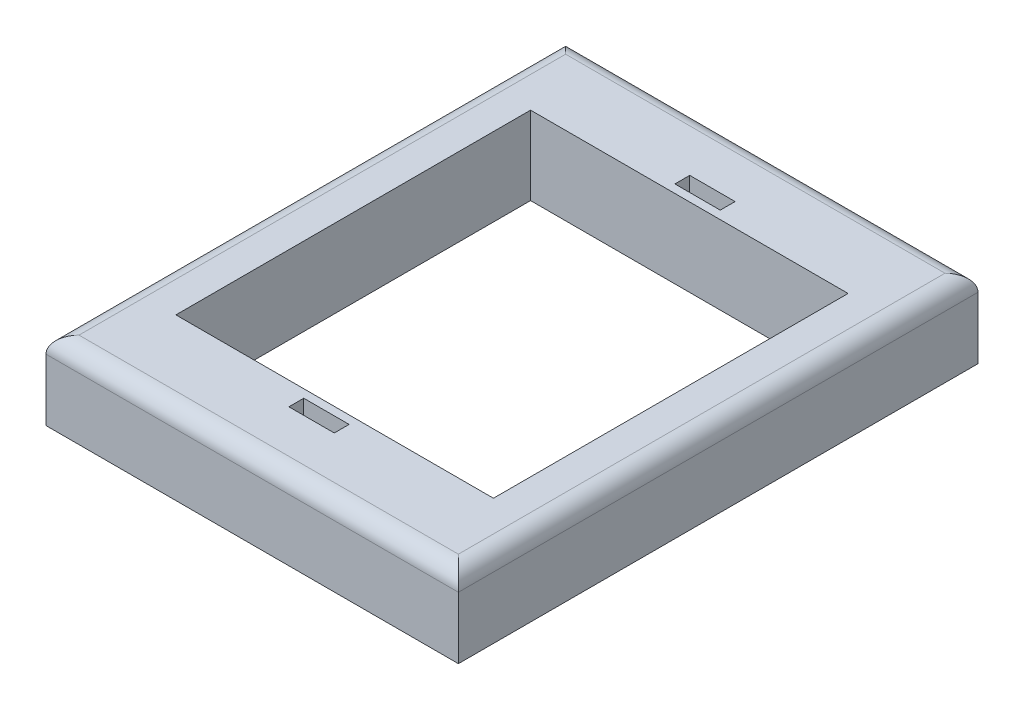
SolidWorks part; units mm, degrees
ref_plane "Front Plane" through (0, 0, 0) normal (0, 0, 1) x (1, 0, 0)
ref_plane "Top Plane" through (0, 0, 0) normal (0, 1, 0) x (1, 0, 0)
ref_plane "Right Plane" through (0, 0, 0) normal (1, 0, 0) x (0, 0, -1)
sketch "Sketch1" plane through (0, 0, 0) normal (0, 1, 0) x (1, 0, 0)
  line L0 (-4.2097, 29.6431) -> (-42.7097, 29.6431)
  line L1 (-42.7097, 29.6431) -> (-42.7097, -13.3569)
  line L2 (-42.7097, -13.3569) -> (-4.2097, -13.3569)
  line L3 (-4.2097, 29.6431) -> (-4.2097, -13.3569)
  line L4 (-48.4597, 39.6431) -> (1.5403, 39.6431)
  line L5 (1.5403, 39.6431) -> (1.5403, -23.3569)
  line L6 (1.5403, -23.3569) -> (-48.4597, -23.3569)
  line L7 (-48.4597, -23.3569) -> (-48.4597, 39.6431)
  dimension "D1" = 43
  dimension "D2" = 38.5
  dimension "D3" = 50
  dimension "D4" = 5.75
  dimension "D5" = 10
  dimension "D6" = 10
extrude "Boss-Extrude1" add sketch "Sketch1" along normal blind 9.5
sketch "Sketch2" plane through (0, 9.5, 0) normal (0, 1, 0) x (1, 0, 0)
  line L0 (-42.7097, -13.3569) -> (-4.2097, -13.3569) construction
  line L1 (-26.2097, 32.4431) -> (-20.7097, 32.4431)
  line L2 (-26.2097, 32.4431) -> (-26.2097, 30.6431)
  line L3 (-26.2097, 30.6431) -> (-20.7097, 30.6431)
  line L4 (-20.7097, 32.4431) -> (-20.7097, 30.6431)
  line L5 (-26.2097, -14.3569) -> (-20.7097, -14.3569)
  line L6 (-26.2097, -14.3569) -> (-26.2097, -16.1569)
  line L7 (-26.2097, -16.1569) -> (-20.7097, -16.1569)
  line L8 (-20.7097, -14.3569) -> (-20.7097, -16.1569)
  line L9 (-4.2097, -13.3569) -> (-4.2097, 29.6431) construction
  dimension "D1" = 45
  dimension "D2" = 1
  dimension "D3" = 5.5
  dimension "D4" = 5.5
  dimension "D5" = 1.8
  dimension "D6" = 1.8
  dimension "D7" = 16.5
  dimension "D8" = 16.5
extrude "Cut-Extrude1" cut sketch "Sketch2" against normal through all
fillet "Fillet1" radius 2 4 edges at (-48.4597, 9.5, -8.1431) (-23.4597, 9.5, 23.3569) (1.5403, 9.5, -8.1431) (-23.4597, 9.5, -39.6431)
